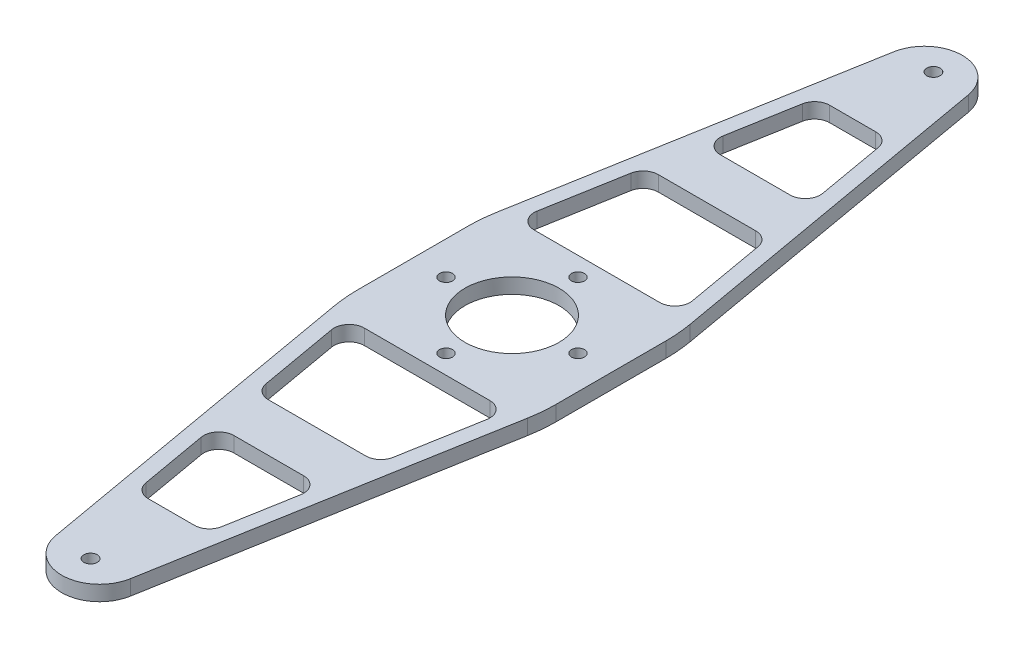
SolidWorks part; units mm, degrees
ref_plane "Front Plane" through (0, 0, 0) normal (0, 0, 1) x (1, 0, 0)
ref_plane "Top Plane" through (0, 0, 0) normal (0, 1, 0) x (1, 0, 0)
ref_plane "Right Plane" through (0, 0, 0) normal (1, 0, 0) x (0, 0, -1)
sketch "Sketch1" plane through (0, 0, 0) normal (0, 1, 0) x (1, 0, 0)
  line L0 (0, -148.5232) -> (0, 148.5232) construction
  line L4 (-12.3101, 138.1938) -> (-31.9504, 26.808)
  line L5 (-32.71, 18.1256) -> (-32.71, -18.1256)
  line L6 (32.71, 18.1256) -> (32.71, -18.1256)
  line L7 (12.3101, 138.1938) -> (31.9504, 26.808)
  line L8 (-55, 0) -> (55, 0) construction
  line L9 (-12.3101, -138.1938) -> (-31.9504, -26.808)
  line L10 (12.3101, -138.1938) -> (31.9504, -26.808)
  line L11 (12.5128, 108.2505) -> (16.4223, 86.0785)
  line L16 (-12.5128, 108.2505) -> (-16.4223, 86.0785)
  line L17 (-7.5887, 112.3822) -> (7.5887, 112.3822)
  line L18 (-11.4982, 80.2103) -> (11.4982, 80.2103)
  line L19 (-16.0653, 64.3095) -> (16.0653, 64.3095)
  line L20 (-20.7026, 28.0097) -> (20.7026, 28.0097)
  line L21 (-20.9893, 60.1778) -> (-25.6267, 33.8779)
  line L22 (-7.3861, 137.3255) -> (-27.0264, 25.9397) construction
  line L23 (20.9893, 60.1778) -> (25.6267, 33.8779)
  line L24 (7.3861, 137.3255) -> (27.0264, 25.9397) construction
  line L25 (-27.71, 18.1256) -> (-27.71, -18.1256) construction
  line L26 (-7.3861, -137.3255) -> (-27.0264, -25.9397) construction
  line L27 (7.3861, -137.3255) -> (27.0264, -25.9397) construction
  line L28 (27.71, 18.1256) -> (27.71, -18.1256) construction
  line L29 (-7.5887, -112.3822) -> (7.5887, -112.3822)
  line L30 (-12.5128, -108.2505) -> (-16.4223, -86.0785)
  line L31 (-11.4982, -80.2103) -> (11.4982, -80.2103)
  line L32 (12.5128, -108.2505) -> (16.4223, -86.0785)
  line L33 (-20.9893, -60.1778) -> (-25.6267, -33.8779)
  line L34 (-20.7026, -28.0097) -> (20.7026, -28.0097)
  line L35 (20.9893, -60.1778) -> (25.6267, -33.8779)
  line L36 (-16.0653, -64.3095) -> (16.0653, -64.3095)
  arc A0 (12.3101, 138.1938) -> (-12.3101, 138.1938) centre (0, 136.0232) ccw
  arc A1 (-31.9504, 26.808) -> (-32.71, 18.1256) centre (17.29, 18.1256) ccw
  arc A2 (31.9504, 26.808) -> (32.71, 18.1256) centre (-17.29, 18.1256) cw
  arc A3 (-31.9504, -26.808) -> (-32.71, -18.1256) centre (17.29, -18.1256) cw
  arc A4 (12.3101, -138.1938) -> (-12.3101, -138.1938) centre (0, -136.0232) cw
  arc A5 (31.9504, -26.808) -> (32.71, -18.1256) centre (-17.29, -18.1256) ccw
  arc A12 (7.3861, 137.3255) -> (-7.3861, 137.3255) centre (0, 136.0232) ccw construction
  arc A13 (27.0264, 25.9397) -> (27.71, 18.1256) centre (-17.29, 18.1256) cw construction
  arc A14 (-27.0264, 25.9397) -> (-27.71, 18.1256) centre (17.29, 18.1256) ccw construction
  arc A15 (-27.0264, -25.9397) -> (-27.71, -18.1256) centre (17.29, -18.1256) cw construction
  arc A16 (7.3861, -137.3255) -> (-7.3861, -137.3255) centre (0, -136.0232) cw construction
  arc A17 (27.0264, -25.9397) -> (27.71, -18.1256) centre (-17.29, -18.1256) ccw construction
  arc A18 (7.5887, 112.3822) -> (12.5128, 108.2505) centre (7.5887, 107.3822) cw
  arc A19 (-7.5887, 112.3822) -> (-12.5128, 108.2505) centre (-7.5887, 107.3822) ccw
  arc A20 (-11.4982, 80.2103) -> (-16.4223, 86.0785) centre (-11.4982, 85.2103) cw
  arc A21 (11.4982, 80.2103) -> (16.4223, 86.0785) centre (11.4982, 85.2103) ccw
  arc A22 (20.7026, 28.0097) -> (25.6267, 33.8779) centre (20.7026, 33.0097) ccw
  arc A23 (16.0653, 64.3095) -> (20.9893, 60.1778) centre (16.0653, 59.3095) cw
  arc A24 (-16.0653, 64.3095) -> (-20.9893, 60.1778) centre (-16.0653, 59.3095) ccw
  arc A25 (-20.7026, 28.0097) -> (-25.6267, 33.8779) centre (-20.7026, 33.0097) cw
  arc A26 (7.5887, -112.3822) -> (12.5128, -108.2505) centre (7.5887, -107.3822) ccw
  arc A27 (-7.5887, -112.3822) -> (-12.5128, -108.2505) centre (-7.5887, -107.3822) cw
  arc A28 (-11.4982, -80.2103) -> (-16.4223, -86.0785) centre (-11.4982, -85.2103) ccw
  arc A29 (11.4982, -80.2103) -> (16.4223, -86.0785) centre (11.4982, -85.2103) cw
  arc A30 (-16.0653, -64.3095) -> (-20.9893, -60.1778) centre (-16.0653, -59.3095) cw
  arc A31 (-20.7026, -28.0097) -> (-25.6267, -33.8779) centre (-20.7026, -33.0097) ccw
  arc A32 (20.7026, -28.0097) -> (25.6267, -33.8779) centre (20.7026, -33.0097) cw
  arc A33 (16.0653, -64.3095) -> (20.9893, -60.1778) centre (16.0653, -59.3095) ccw
  point P8 (0, 0)
  point P23 (-32.71, 22.5)
  point P31 (-32.71, 0)
  point P39 (32.71, 0)
  point P69 (26.6614, 28.0097)
  point P72 (20.2607, 64.3095)
  point P75 (-20.2607, 64.3095)
  point P78 (-26.6614, 28.0097)
  dimension "D1" = 25
  dimension "D4" = 50
  dimension "D6" = 5
  dimension "D2" = 10
  dimension "D3" = 22.5
  dimension "D5" = 5
extrude "Boss-Extrude1" add sketch "Sketch1" along normal blind 5
sketch "Sketch2" plane through (0, 5, 0) normal (0, 1, 0) x (1, 0, 0)
  line L1 (0, 15.5) -> (0, 28.0097) construction
  line L2 (-20.7026, 28.0097) -> (20.7026, 28.0097) construction
  circle A0 centre (0, 0) radius 15.5
  circle A1 centre (0, 21.7549) radius 2.15
  circle A2 centre (21.7549, 0) radius 2.15
  circle A3 centre (0, -21.7549) radius 2.15
  circle A4 centre (-21.7549, 0) radius 2.15
  point P18 (0, 0)
  dimension "D1" = 31
  dimension "D3" = 4.3
  dimension "D2" = 4
extrude "Cut-Extrude1" cut sketch "Sketch2" against normal through all both and the other way through all
sketch "Sketch3" plane through (0, 0, 0) normal (0, -1, 0) x (1, 0, 0)
  line L0 (0, 139) -> (0, -139) construction
  circle A0 centre (0, -139) radius 2.2
  circle A1 centre (0, 139) radius 2.2
  point P6 (0, 0)
  dimension "D1" = 4.4
  dimension "D2" = 278
extrude "Cut-Extrude2" cut sketch "Sketch3" against normal through all both and the other way through all
